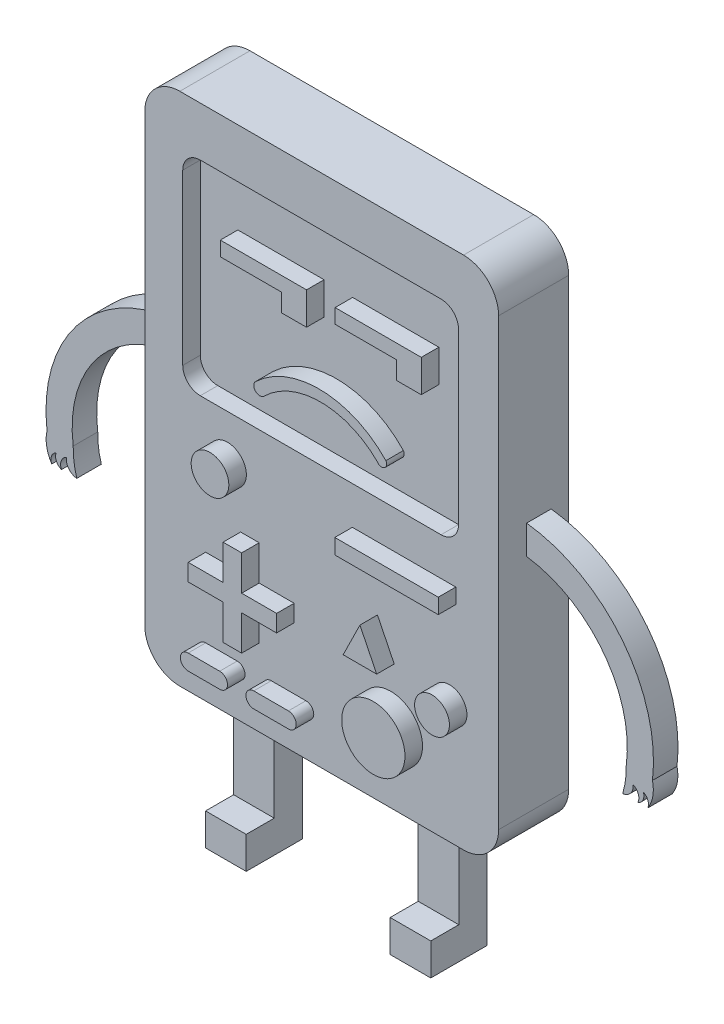
SolidWorks part; units mm, degrees
ref_plane "Alzado" through (0, 0, 0) normal (0, 0, 1) x (1, 0, 0)
ref_plane "Planta" through (0, 0, 0) normal (0, 1, 0) x (1, 0, 0)
ref_plane "Vista lateral" through (0, 0, 0) normal (1, 0, 0) x (0, 0, -1)
sketch "Croquis2" plane through (0, 0, 0) normal (0, 0, 1) x (1, 0, 0)
  line L0 (-70.6965, 2.6635) -> (51.9702, 2.6635) construction
  line L1 (14.8644, -4.5648) -> (36.0169, -4.5648)
  line L2 (36.044, -22.2986) -> (24.1975, -22.2986)
  line L3 (25.4854, -52.4713) -> (-2.6364, -52.4713)
  line L4 (-6.0317, -66.6641) -> (-6.0317, -73.1048)
  line L6 (125.9488, 73.8312) -> (206.8604, 73.8312)
  line L7 (115.9488, 63.8312) -> (115.9488, -63.1048)
  line L8 (125.9488, -73.1048) -> (206.8604, -73.1048)
  line L9 (216.8604, 63.8312) -> (216.8604, -63.1048)
  line L10 (115.9488, 73.8312) -> (216.8604, -73.1048) construction
  line L11 (115.9488, -73.1048) -> (216.8604, 73.8312) construction
  arc A0 (-41.9236, -14.6699) -> (-41.216, -30.4304) centre (-47.1707, -22.8016) ccw
  arc A1 (-50.4594, -21.0121) -> (-43.3833, -22.2986) centre (-47.5647, -25.1934) cw
  arc A2 (-47.1707, -32.4792) -> (-49.5714, -61.7426) centre (-197.0161, -34.9164) cw
  arc A3 (-66.5107, 78.9925) -> (-48.977, -13.294) centre (-334.446, -19.7219) cw
  arc A4 (-66.5107, 78.9925) -> (-55.3894, 74.4745) centre (-66.7798, 62.3834) cw
  arc A5 (-55.3894, 74.4745) -> (-52.2615, 86.1171) centre (-25.7128, 72.7431) cw
  arc A6 (-43.4032, 78.9925) -> (-52.2615, 86.1171) centre (-79.8626, 42.73) ccw
  arc A7 (-43.4032, 78.9925) -> (-41.216, 89.9401) centre (-10.3032, 78.0718) cw
  arc A8 (-41.216, 89.9401) -> (-32.7992, 80.904) centre (-60.6048, 63.4422) cw
  arc A9 (-32.7992, 80.904) -> (-27.5861, 92.8942) centre (-5.5462, 76.1832) cw
  arc A10 (-27.5861, 92.8942) -> (-20.4615, 84.5591) centre (-82.1194, 39.0679) cw
  arc A11 (-20.4615, 84.5591) -> (-14.7271, 95.8483) centre (69.9669, 45.7261) cw
  arc A12 (-14.7271, 95.8483) -> (-8.4713, 84.5591) centre (-41.7329, 73.5055) cw
  arc A13 (-8.4713, 84.5591) -> (-2.9107, 95.8483) centre (20.0765, 77.5115) cw
  arc A14 (-2.9107, 95.8483) -> (3.6926, 87.2115) centre (-10.4832, 83.216) cw
  arc A15 (3.6926, 87.2115) -> (10.9279, 95.8483) centre (54.5163, 51.9837) cw
  arc A16 (10.9279, 95.8483) -> (17.0729, 87.2115) centre (-0.9144, 80.918) cw
  arc A17 (17.0729, 87.2115) -> (24.1975, 94.1106) centre (41.23, 69.3929) cw
  arc A18 (24.1975, 94.1106) -> (29.0631, 84.5591) centre (317.216, 237.3616) ccw
  arc A19 (29.0631, 84.5591) -> (35.8402, 91.9658) centre (51.3775, 70.9453) cw
  arc A20 (35.8402, 91.9658) -> (39.1418, 36.0712) centre (-5697.8002, -274.7599) cw
  arc A21 (39.1418, 36.0712) -> (44.493, 24.4399) centre (36.0018, 27.5799) cw
  arc A22 (14.5073, 21.3572) -> (42.9191, -7.8127) centre (30.9355, 8.9368) cw
  circle A23 centre (-4.2715, 8.1351) radius 22.9667
  arc A24 (36.0169, -4.5648) -> (36.044, -22.2986) centre (36.0598, -13.4317) cw
  arc A25 (43.9876, -17.4033) -> (49.0939, -41.4446) centre (186.7845, 0.3632) ccw
  arc A26 (49.0939, -41.4446) -> (25.4854, -52.4713) centre (24.4378, -19.4419) cw
  arc A27 (-2.6364, -52.4713) -> (-24.7002, -46.3916) centre (-2.6364, -9.3956) cw
  arc A28 (-29.2973, -49.2528) -> (-21.2393, -45.1531) centre (-15.7926, -65.8275) cw
  circle A29 centre (-9.8099, 6.5936) radius 3.3632
  circle A30 centre (30.9355, 7.2099) radius 2.8479
  arc A31 (-49.5714, -61.7426) -> (-6.0317, -73.1048) centre (-1.3144, 34.0741) ccw
  arc A32 (24.1975, -22.2986) -> (0, -14.4308) centre (23.2606, 15.9637) cw
  arc A33 (206.8604, -73.1048) -> (216.8604, -63.1048) centre (206.8604, -63.1048) ccw
  arc A34 (115.9488, -63.1048) -> (125.9488, -73.1048) centre (125.9488, -63.1048) ccw
  arc A35 (206.8604, 73.8312) -> (216.8604, 63.8312) centre (206.8604, 63.8312) cw
  arc A36 (125.9488, 73.8312) -> (115.9488, 63.8312) centre (125.9488, 63.8312) ccw
  spline S0 degree 2 poles (-48.015, -25.7724) (-48.0751, -22.7108) (-46.2208, -20.2885) knots 0 0 0 1 1 1
  spline S1 degree 3 poles (6.8497, -52.4713) (9.0558, -61.0328) (-6.2942, -57.9048) (-6.0317, -66.6641) knots 0 0 0 0 1 1 1 1
  point P84 (166.4046, 0.3632)
  dimension "D1" = 10
extrude "Saliente-Extruir1" add sketch "Croquis2" along normal blind 20 contours L6 A36 L7 A34 L8 A33 L9 A35
sketch "Croquis3" plane through (0, 0, 20) normal (0, 0, 1) x (1, 0, 0)
  line L1 (131.7772, 1.5433) -> (200.4492, 1.5433)
  line L2 (126.7772, 6.5433) -> (126.7772, 54.7606)
  line L3 (131.7772, 59.7606) -> (200.4492, 59.7606)
  line L4 (205.4492, 6.5433) -> (205.4492, 54.7606)
  line L5 (126.7772, 1.5433) -> (205.4492, 59.7606) construction
  line L6 (126.7772, 59.7606) -> (205.4492, 1.5433) construction
  arc A0 (131.7772, 1.5433) -> (126.7772, 6.5433) centre (131.7772, 6.5433) cw
  arc A1 (200.4492, 1.5433) -> (205.4492, 6.5433) centre (200.4492, 6.5433) ccw
  arc A2 (200.4492, 59.7606) -> (205.4492, 54.7606) centre (200.4492, 54.7606) cw
  arc A3 (126.7772, 54.7606) -> (131.7772, 59.7606) centre (131.7772, 54.7606) cw
  point P0 (166.1132, 30.6519)
  dimension "D1" = 5
extrude "Cortar-Extruir1" cut sketch "Croquis3" against normal blind 5
sketch "Croquis4" plane through (0, 0, 20) normal (0, 0, 1) x (1, 0, 0)
  line L1 (204.6531, -9.2741) -> (175.1511, -9.2741)
  line L2 (204.6531, -9.2741) -> (204.6531, -13.6011)
  line L3 (204.6531, -13.6011) -> (175.1511, -13.6011)
  line L4 (175.1511, -9.2741) -> (175.1511, -13.6011)
  line L5 (204.6531, -9.2741) -> (175.1511, -13.6011) construction
  line L6 (204.6531, -13.6011) -> (175.1511, -9.2741) construction
  line L7 (143.2857, -26.3684) -> (148.5825, -26.3684)
  line L8 (133.3216, -36.3325) -> (133.3216, -41.173)
  line L9 (143.2857, -51.1372) -> (148.5825, -51.1372)
  line L10 (158.5467, -36.3325) -> (158.5467, -41.173)
  line L11 (131.7511, -26.1886) -> (148.5825, -42.6032) construction
  line L12 (143.2857, -40.4454) -> (148.5825, -37.0601) construction
  line L15 (158.5467, -36.3325) -> (148.5825, -36.3325)
  line L16 (148.5825, -26.3684) -> (148.5825, -36.3325)
  line L17 (143.2857, -26.3684) -> (143.2857, -36.3325)
  line L18 (143.2857, -36.3325) -> (133.3216, -36.3325)
  line L20 (143.2857, -41.173) -> (133.3216, -41.173)
  line L21 (143.2857, -41.173) -> (143.2857, -51.1372)
  line L24 (158.5467, -41.173) -> (148.5825, -41.173)
  line L27 (148.5825, -41.173) -> (148.5825, -51.1372)
  line L28 (177.5318, -37.0601) -> (182.3127, -27.3361)
  line L29 (177.5318, -37.0601) -> (187.0937, -37.0601)
  line L33 (187.0937, -37.0601) -> (182.3127, -27.3361)
  line L34 (133.3216, -60.9623) -> (142.312, -60.9623) construction
  line L35 (133.3216, -58.7311) -> (142.312, -58.7311)
  line L36 (133.3216, -63.1934) -> (142.312, -63.1934)
  line L37 (152.0333, -60.9623) -> (161.914, -60.9623) construction
  line L38 (152.0333, -58.7311) -> (161.914, -58.7311)
  line L39 (152.0333, -63.1934) -> (161.914, -63.1934)
  circle A0 centre (139.552, -11.4376) radius 5.3719
  circle A1 centre (202.8709, -39.2546) radius 4.9647
  circle A2 centre (186.1375, -53.3127) radius 9.0207
  arc A3 (133.3216, -58.7311) -> (133.3216, -63.1934) centre (133.3216, -60.9623) ccw
  arc A4 (142.312, -63.1934) -> (142.312, -58.7311) centre (142.312, -60.9623) ccw
  arc A5 (152.0333, -58.7311) -> (152.0333, -63.1934) centre (152.0333, -60.9623) ccw
  arc A6 (161.914, -63.1934) -> (161.914, -58.7311) centre (161.914, -60.9623) ccw
  point P0 (189.9021, -11.4376)
  point P7 (145.1489, -39.2546)
  point P33 (137.8168, -60.9623)
  point P38 (156.9736, -60.9623)
extrude "Saliente-Extruir2" add sketch "Croquis4" along normal blind 5
ref_plane "Plano1" through (0, 0, 5) normal (0, 0, 1) x (1, 0, 0)
sketch "Croquis5" plane through (0, 0, 5) normal (0, 0, 1) x (1, 0, 0)
  line L0 (216.8604, 63.8312) -> (216.8604, -63.1048) construction
  line L1 (216.8604, 0.3632) -> (216.8604, 8.6237)
  line L2 (166.4046, 73.8312) -> (166.4046, -104.4294) construction
  line L3 (125.9488, 73.8312) -> (206.8604, 73.8312) construction
  line L4 (115.9488, 0.3632) -> (115.9488, 8.6237)
  arc A0 (216.8604, 0.3632) -> (245.2733, -37.006) centre (212.3823, -32.5278) cw
  arc A1 (216.8604, 8.6237) -> (252.7471, -37.006) centre (211.9889, -32.1345) cw
  arc A2 (245.2733, -37.006) -> (244.254, -44.4923) centre (221.1721, -37.5372) cw
  arc A3 (244.254, -44.4923) -> (247.233, -40.7894) centre (243.892, -41.1513) ccw
  arc A4 (247.233, -40.7894) -> (248.6109, -44.4923) centre (246.0705, -43.3298) cw
  arc A5 (248.6109, -44.4923) -> (250.1398, -41.1513) centre (247.7048, -42.0574) ccw
  arc A6 (250.1398, -41.1513) -> (251.383, -44.4923) centre (249.0909, -43.4434) cw
  arc A7 (251.383, -44.4923) -> (252.7471, -37.006) centre (243.4597, -39.1811) ccw
  arc A8 (115.9488, 0.3632) -> (87.5359, -37.006) centre (120.4269, -32.5278) ccw
  arc A9 (115.9488, 8.6237) -> (80.0621, -37.006) centre (120.8203, -32.1345) ccw
  arc A10 (81.4262, -44.4923) -> (80.0621, -37.006) centre (89.3495, -39.1811) cw
  arc A11 (82.6694, -41.1513) -> (81.4262, -44.4923) centre (83.7183, -43.4434) ccw
  arc A12 (84.1983, -44.4923) -> (82.6694, -41.1513) centre (85.1044, -42.0574) cw
  arc A13 (85.5762, -40.7894) -> (84.1983, -44.4923) centre (86.7387, -43.3298) ccw
  arc A14 (88.5552, -44.4923) -> (85.5762, -40.7894) centre (88.9172, -41.1513) cw
  arc A15 (87.5359, -37.006) -> (88.5552, -44.4923) centre (111.6371, -37.5372) ccw
extrude "Saliente-Extruir3" add sketch "Croquis5" along normal blind 7
sketch "Croquis6" plane through (0, 0, 15) normal (0, 0, 1) x (1, 0, 0)
  line L0 (170.2291, 42.5466) -> (187.7336, 42.5466)
  line L1 (137.4926, 42.8461) -> (154.9972, 42.8461)
  line L2 (137.4926, 42.8461) -> (137.4926, 38.7158)
  line L3 (137.4926, 38.7158) -> (154.9972, 38.7158)
  line L5 (154.9972, 42.8461) -> (162.0776, 42.8461)
  line L6 (154.9972, 38.7158) -> (154.9972, 33.6021)
  line L7 (154.9972, 33.6021) -> (162.0776, 33.6021)
  line L8 (162.0776, 42.8461) -> (162.0776, 33.6021)
  line L9 (170.2291, 42.5466) -> (170.2291, 38.4163)
  line L10 (170.2291, 38.4163) -> (187.7336, 38.4163)
  line L11 (187.7336, 42.5466) -> (194.8141, 42.5466)
  line L12 (187.7336, 38.4163) -> (187.7336, 33.3027)
  line L13 (187.7336, 33.3027) -> (194.8141, 33.3027)
  line L14 (194.8141, 42.5466) -> (194.8141, 33.3027)
  arc A0 (147.6067, 12.9854) -> (184.7146, 11.9722) centre (165.654, -6.0751) cw
  arc A1 (149.8863, 10.4525) -> (182.3082, 10.4525) centre (166.0973, -5.7585) cw
  arc A2 (147.6067, 12.9854) -> (149.8863, 10.4525) centre (148.7465, 11.7189) ccw
  arc A3 (184.7146, 11.9722) -> (182.3082, 10.4525) centre (183.5114, 11.2123) cw
extrude "Saliente-Extruir4" add sketch "Croquis6" along normal blind 5
sketch "Croquis8" plane through (0, 0, 5) normal (0, 0, 1) x (1, 0, 0)
  line L0 (198.5155, -73.1048) -> (198.5155, -108.4094)
  line L1 (125.9488, -73.1048) -> (206.8604, -73.1048) construction
  line L2 (198.5155, -108.4094) -> (186.9365, -108.4094)
  line L3 (186.9365, -108.4094) -> (186.9365, -73.1048)
  line L4 (186.9365, -73.1048) -> (198.5155, -73.1048)
  line L5 (166.4046, -73.1048) -> (166.4046, 132.9358) construction
  line L6 (145.8727, -73.1048) -> (134.2937, -73.1048)
  line L7 (145.8727, -108.4094) -> (145.8727, -73.1048)
  line L8 (134.2937, -73.1048) -> (134.2937, -108.4094)
  line L9 (134.2937, -108.4094) -> (145.8727, -108.4094)
  point P8 (166.4046, -73.1048)
  point P9 (166.4046, -73.1048)
extrude "Saliente-Extruir5" add sketch "Croquis8" along normal blind 8
ref_plane "Plano2" through (0, 0, 13) normal (0, 0, 1) x (1, 0, 0)
sketch "Croquis10" plane through (0, 0, 13) normal (0, 0, 1) x (1, 0, 0)
  line L0 (134.2937, -73.1048) -> (134.2937, -108.4094) construction
  line L1 (134.2937, -99.2518) -> (145.8727, -99.2518)
  line L2 (134.2937, -99.2518) -> (134.2937, -108.4094)
  line L3 (134.2937, -108.4094) -> (145.8727, -108.4094)
  line L4 (145.8727, -99.2518) -> (145.8727, -108.4094)
  line L5 (186.9365, -73.1048) -> (186.9365, -108.4094) construction
  line L6 (186.9365, -99.2518) -> (198.5155, -99.2518)
  line L7 (186.9365, -99.2518) -> (186.9365, -108.4094)
  line L8 (186.9365, -108.4094) -> (198.5155, -108.4094)
  line L9 (198.5155, -99.2518) -> (198.5155, -108.4094)
extrude "Saliente-Extruir6" add sketch "Croquis10" along normal blind 8
